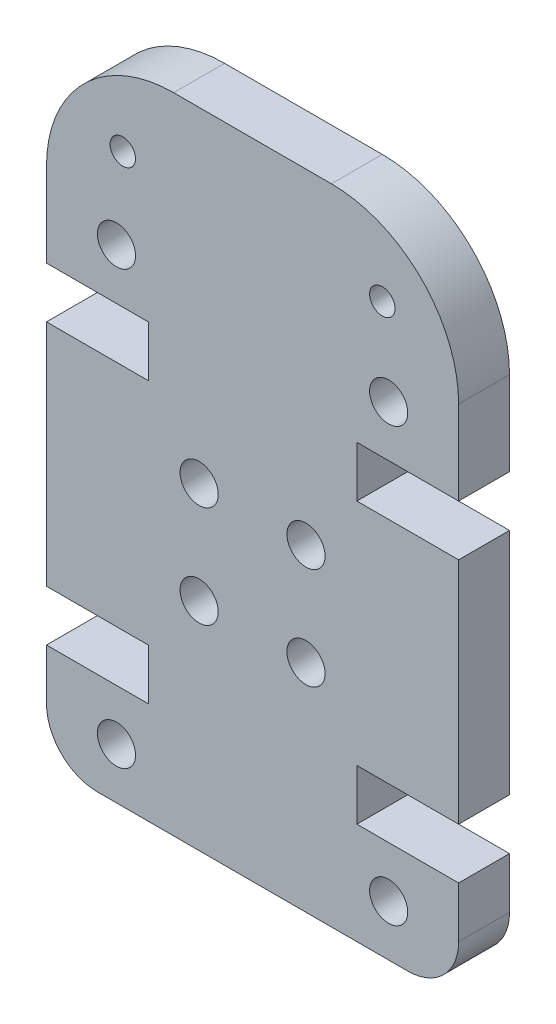
SolidWorks part; units mm, degrees
ref_plane "Front Plane" through (0, 0, 0) normal (0, 0, 1) x (1, 0, 0)
ref_plane "Top Plane" through (0, 0, 0) normal (0, 1, 0) x (1, 0, 0)
ref_plane "Right Plane" through (0, 0, 0) normal (1, 0, 0) x (0, 0, -1)
sketch "Sketch1" plane through (0, 0, 0) normal (0, 0, 1) x (1, 0, 0)
  line L20 (0, 6) -> (0, 15)
  line L21 (16.2, 6) -> (16.2, 15)
  line L22 (0, 20.3) -> (0, 17)
  line L23 (16.2, 20.3) -> (16.2, 17)
  line L24 (16.2, 15) -> (12.2, 15)
  line L25 (12.2, 15) -> (12.2, 17)
  line L26 (4, 17) -> (0, 17)
  line L27 (4, 15) -> (4, 17)
  line L28 (12.2, 17) -> (16.2, 17)
  line L29 (0, 15) -> (4, 15)
  line L30 (5, 25.3) -> (11.2, 25.3)
  line L31 (2, 0) -> (14.2, 0)
  line L32 (16.2, 2) -> (16.2, 4)
  line L33 (0, 2) -> (0, 4)
  line L34 (0, 6) -> (4, 6)
  line L35 (12.2, 4) -> (16.2, 4)
  line L36 (4, 6) -> (4, 4)
  line L37 (4, 4) -> (0, 4)
  line L38 (12.2, 6) -> (12.2, 4)
  line L39 (16.2, 6) -> (12.2, 6)
  circle A10 centre (6, 12.5) radius 0.75
  circle A11 centre (10.2, 12.5) radius 0.75
  circle A12 centre (2.75, 19) radius 0.75
  circle A13 centre (13.45, 19) radius 0.75
  circle A14 centre (10.2, 8.5) radius 0.75
  circle A15 centre (6, 8.5) radius 0.75
  arc A16 (14.2, 0) -> (16.2, 2) centre (14.2, 2) ccw
  arc A17 (5, 25.3) -> (0, 20.3) centre (5, 20.3) ccw
  arc A18 (16.2, 20.3) -> (11.2, 25.3) centre (11.2, 20.3) ccw
  circle A19 centre (3, 22.3) radius 0.5
  circle A20 centre (13.2, 22.3) radius 0.5
  arc A21 (0, 2) -> (2, 0) centre (2, 2) ccw
  circle A22 centre (13.45, 2) radius 0.75
  circle A23 centre (2.75, 2) radius 0.75
extrude "Boss-Extrude1" add sketch "Sketch1" along normal blind 2
